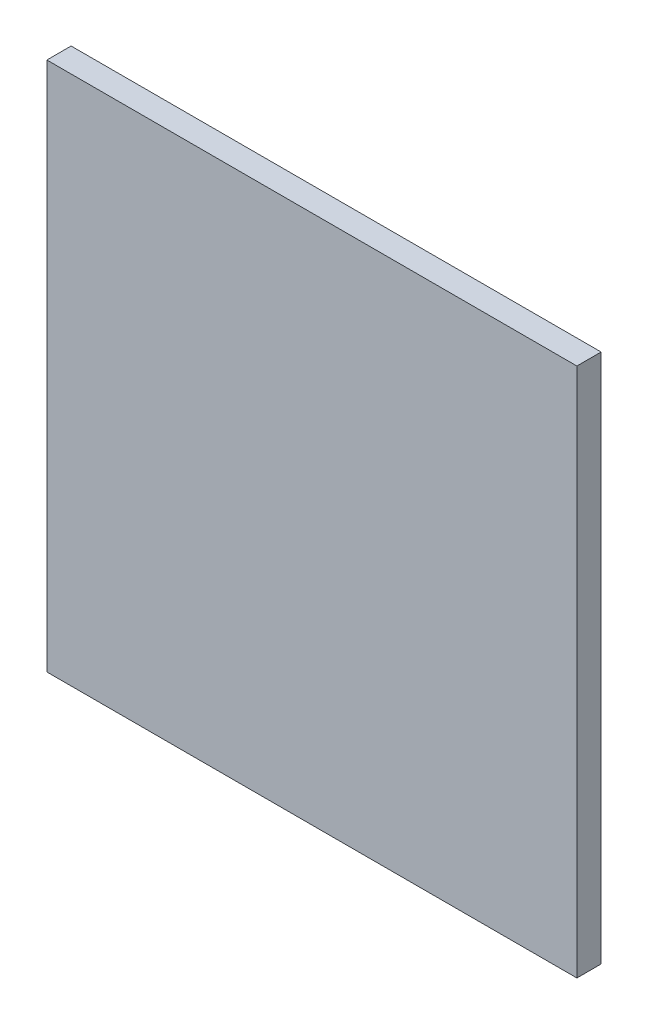
SolidWorks part; units mm, degrees
ref_plane "Plano frontal" through (0, 0, 0) normal (0, 0, 1) x (1, 0, 0)
ref_plane "Plano superior" through (0, 0, 0) normal (0, 1, 0) x (1, 0, 0)
ref_plane "Plano direito" through (0, 0, 0) normal (1, 0, 0) x (0, 0, -1)
sketch "Esboço1" plane through (0, 0, 0) normal (0, 0, 1) x (1, 0, 0)
  line L0 (245, 245) -> (-245, -245) construction
  line L1 (-245, 245) -> (245, 245)
  line L2 (-245, 245) -> (-245, -245)
  line L3 (-245, -245) -> (245, -245)
  line L4 (245, 245) -> (245, -245)
  dimension "D1" = 490
  dimension "D2" = 490
extrude "Ressalto-extrusão1" add sketch "Esboço1" along normal blind 22.4
